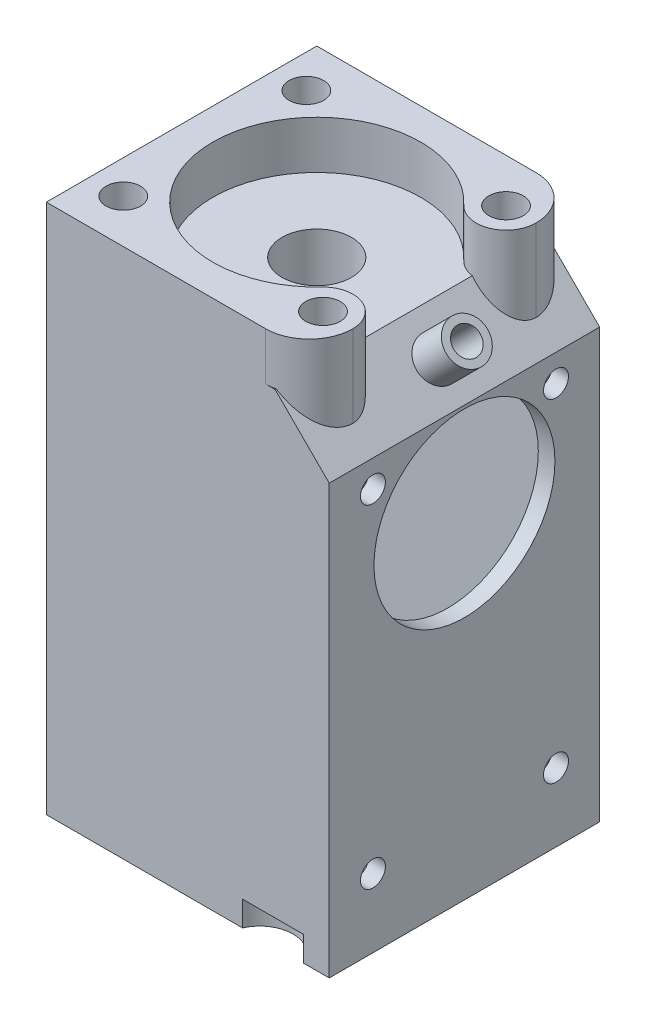
SolidWorks part; units mm, degrees
ref_plane "Front Plane" through (0, 0, 0) normal (0, 0, 1) x (1, 0, 0)
ref_plane "Top Plane" through (0, 0, 0) normal (0, 1, 0) x (1, 0, 0)
ref_plane "Right Plane" through (0, 0, 0) normal (1, 0, 0) x (0, 0, -1)
sketch "Sketch1" plane through (0, 0, 0) normal (1, 0, 0) x (0, 0, -1)
  line L0 (0, 55) -> (0, -55) construction
  line L1 (-14.25, -23.25) -> (14.25, -23.25)
  line L2 (-14.25, -23.25) -> (-14.25, 23.25)
  line L3 (-14.25, 23.25) -> (14.25, 23.25)
  line L4 (14.25, -23.25) -> (14.25, 23.25)
  line L5 (-14.25, -23.25) -> (14.25, 23.25) construction
  line L6 (-14.25, 23.25) -> (14.25, -23.25) construction
  line L7 (55, 0) -> (-55, 0) construction
  line L8 (0, 23.25) -> (0, -23.25) construction
  circle A0 centre (-11, 20) radius 1.5
  circle A1 centre (11, 20) radius 1.5
  circle A2 centre (11, -20) radius 1.5
  circle A3 centre (-11, -20) radius 1.5
  circle A4 centre (0, 12) radius 10.875
  point P0 (0, 0)
  dimension "D5" = 3
  dimension "D7" = 21.75
  dimension "D1" = 28.5
  dimension "D2" = 46.5
  dimension "D3" = 3.25
  dimension "D4" = 3.25
  dimension "D6" = 11.25
extrude "Boss-Extrude1" add sketch "Sketch1" along normal mid plane 2
sketch "Sketch2" plane through (0, 23.25, 0) normal (0, 1, 0) x (1, 0, 0)
  line L0 (1, -14.25) -> (-1, -14.25) construction
  line L1 (1, 14.25) -> (-33, 14.25)
  line L2 (1, 14.25) -> (1, -14.25)
  line L3 (1, -14.25) -> (-33, -14.25)
  line L4 (-33, 14.25) -> (-33, -14.25)
  dimension "D1" = 34
extrude "Boss-Extrude2" add sketch "Sketch2" along normal blind 6.5
sketch "Sketch4" plane through (0, 29.75, 0) normal (0, 1, 0) x (1, 0, 0)
  line L0 (1, 0) -> (-33, 0) construction
  line L1 (1, -14.25) -> (1, 14.25) construction
  line L2 (-33, 14.25) -> (-33, -14.25) construction
  circle A0 centre (-16.75, 0) radius 4.175
  dimension "D1" = 8.35
  dimension "D2" = 17.75
extrude "Cut-Extrude1" cut sketch "Sketch4" against normal up to next
sketch "Sketch15" plane through (0, -23.25, 0) normal (0, -1, 0) x (1, 0, 0)
  line L0 (-33, 0) -> (0, 0) construction
  line L1 (1, 14.25) -> (-33, 14.25)
  line L2 (1, 14.25) -> (1, -14.25)
  line L3 (1, -14.25) -> (-33, -14.25)
  line L4 (-33, 14.25) -> (-33, -14.25)
  circle A0 centre (-12.75, 0) radius 2.15
  circle A1 centre (-16.75, 0) radius 4.175 construction
  circle A2 centre (-16.75, 0) radius 4.175 construction
  dimension "D1" = 4
  dimension "D2" = 4.3
extrude "Boss-Extrude8" add sketch "Sketch15" along normal blind 5
chamfer "Chamfer1" distance 6.5 angle 45 1 edges at (1, 29.75, 0)
sketch "Sketch17" plane through (0, 0, 14.25) normal (0, 0, 1) x (1, 0, 0)
  line L0 (-33, 29.75) -> (-33, -28.25)
  line L1 (-33, -28.25) -> (1, -28.25)
  line L2 (1, -28.25) -> (1, 23.25)
  line L3 (1, 23.25) -> (-5.5, 29.75)
  line L4 (-5.5, 29.75) -> (-33, 29.75)
extrude "Boss-Extrude9" add sketch "Sketch17" along normal blind 2
mirror "Mirror3" about plane through (0, 0, 0) normal (0, 0, 1) of "Boss-Extrude9"
sketch "Sketch5" plane through (12.125, 12.125, 0) normal (0.7071, 0.7071, 0) x (0, 0, -1)
  line L0 (0, 24.9255) -> (0, 15.7331) construction
  line L1 (-16.25, 24.9255) -> (16.25, 24.9255) construction
  line L2 (16.25, 15.7331) -> (-16.25, 15.7331) construction
  circle A0 centre (0, 20.3293) radius 2.5
  dimension "D1" = 5
extrude "Boss-Extrude4" add sketch "Sketch5" along normal blind 5
sketch "Sketch7" plane through (15.6605, 15.6605, 0) normal (0.7071, 0.7071, 0) x (0, 0, -1)
  circle A0 centre (0, 20.3293) radius 1.6
  circle A1 centre (0, 20.3293) radius 2.5
  circle A2 centre (0, 20.3293) radius 2.5
  dimension "D2" = 3.2
  dimension "D1" = 0
extrude "Cut-Extrude4" cut sketch "Sketch7" against normal up to surface (5 mm away) contours A0
sketch "Sketch10" plane through (0, 23.25, 0) normal (0, 1, 0) x (1, 0, 0)
  line L0 (-29, 16.25) -> (-29, -16.25) construction
  line L1 (-33, -16.25) -> (-33, 16.25)
  line L2 (-33, 16.25) -> (-6.6546, 16.25)
  line L3 (-5.5, 16.25) -> (-33, 16.25) construction
  line L4 (-33, 0) -> (11.8022, 0) construction
  line L5 (-33, 16.25) -> (-33, -16.25) construction
  line L6 (-5.5, -16.25) -> (-33, -16.25) construction
  line L7 (-33, -16.25) -> (-6.6546, -16.25)
  line L9 (1, -16.25) -> (-5.5, -16.25) construction
  circle A4 centre (-29, 11) radius 2.075
  circle A5 centre (-29, -11) radius 2.075
  circle A6 centre (-5, 11) radius 2.075
  circle A7 centre (-5, -11) radius 2.075
  circle A8 centre (-16.75, 0) radius 12.5 construction
  circle A9 centre (-16.75, 0) radius 4.175 construction
  arc A10 (-7.6247, 8.5428) -> (-7.6247, -8.5428) centre (-16.75, 0) ccw
  arc A11 (-6.6546, -16.25) -> (-1.4046, -11) centre (-6.6546, -11) ccw
  arc A12 (-7.6247, -8.5428) -> (-1.4046, -11) centre (-5, -11) cw
  arc A14 (-7.6247, 8.5428) -> (-1.4046, 11) centre (-5, 11) ccw
  arc A15 (-6.6546, 16.25) -> (-1.4046, 11) centre (-6.6546, 11) cw
  dimension "D2" = 22
  dimension "D4" = 24
  dimension "D5" = 4.15
  dimension "D6" = 11.75
  dimension "D7" = 12.25
  dimension "D8" = 25
  dimension "D1" = 4
  dimension "D3" = 11
extrude "Boss-Extrude6" add sketch "Sketch10" along normal blind 12.25
sketch "Sketch18" plane through (0, 35.5, 0) normal (0, 1, 0) x (1, 0, 0)
  circle A0 centre (-5, -11) radius 2.075 construction
  circle A1 centre (-5, 11) radius 2.075 construction
  circle A2 centre (-5, -11) radius 2.075
  circle A3 centre (-5, 11) radius 2.075
extrude "Cut-Extrude7" cut sketch "Sketch18" against normal blind 10
sketch "Sketch19" plane through (0, -28.25, 0) normal (0, -1, 0) x (1, 0, 0)
  line L0 (0, 0) -> (-49.3665, 0) construction
  line L1 (-27.35, -8.14) -> (-27.35, 8.14) construction
  line L2 (-5.75, -17.85) -> (-5.75, 17.85) construction
  circle A0 centre (-5.75, 17.85) radius 4
  circle A1 centre (-5.75, -17.85) radius 4
  circle A2 centre (-27.35, 8.14) radius 4
  circle A3 centre (-27.35, -8.14) radius 4
  circle A4 centre (-12.75, 0) radius 2.15 construction
  point P14 (-27.35, 0)
  point P17 (-5.75, 0)
  dimension "D1" = 8
  dimension "D4" = 14.6
  dimension "D5" = 7
  dimension "D2" = 16.28
  dimension "D3" = 35.7
extrude "Cut-Extrude8" cut sketch "Sketch19" against normal blind 3
